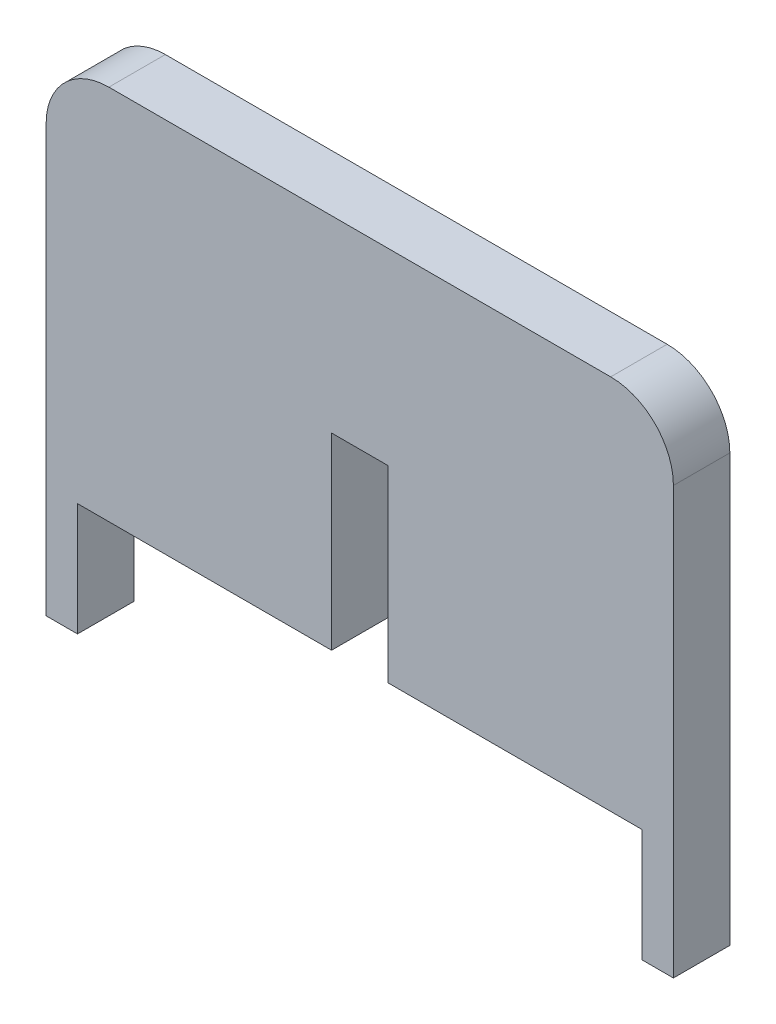
SolidWorks part; units mm, degrees
material "Balsa"
ref_plane "Front Plane" through (0, 0, 0) normal (0, 0, 1) x (1, 0, 0)
ref_plane "Top Plane" through (0, 0, 0) normal (0, 1, 0) x (1, 0, 0)
ref_plane "Right Plane" through (0, 0, 0) normal (1, 0, 0) x (0, 0, -1)
sketch "Sketch1" plane through (0, 0, 0) normal (0, 0, 1) x (1, 0, 0)
  line L0 (-2.25, 0) -> (2.25, 0)
  line L1 (25, -15) -> (-25, -15)
  line L2 (25, -15) -> (25, 15)
  line L3 (25, 15) -> (-25, 15)
  line L4 (-25, -15) -> (-25, 15)
  line L5 (25, -15) -> (-25, 15) construction
  line L6 (25, 15) -> (-25, -15) construction
  line L7 (-2.25, 15) -> (2.25, 15)
  line L8 (-2.25, 15) -> (-2.25, -15)
  line L9 (-2.25, -15) -> (2.25, -15)
  line L10 (2.25, 15) -> (2.25, -15)
  line L11 (-2.25, 15) -> (2.25, -15) construction
  line L12 (-2.25, -15) -> (2.25, 15) construction
  line L13 (-25, -15) -> (-22.5, -15)
  line L14 (-25, -15) -> (-25, -24)
  line L15 (-25, -24) -> (-22.5, -24)
  line L16 (-22.5, -15) -> (-22.5, -24)
  line L17 (25, -15) -> (22.5, -15)
  line L18 (25, -15) -> (25, -24)
  line L19 (25, -24) -> (22.5, -24)
  line L20 (22.5, -15) -> (22.5, -24)
  point P0 (0, 0)
  point P6 (0, 0)
  dimension "D1" = 50
  dimension "D2" = 30
  dimension "D3" = 4.5
  dimension "D4" = 9
  dimension "D5" = 9
  dimension "D6" = 2.5
  dimension "D7" = 2.5
extrude "Boss-Extrude1" add sketch "Sketch1" along normal blind 4.5 contours L8 L3 L4 L1 | L3 L10 L1 L2 | L16 L1 L14 L15 | L1 L20 L19 L18 | L10 L3 L8 L0
fillet "Fillet1" radius 5 2 edges at (25, 15, 2.25) (-25, 15, 2.25)
